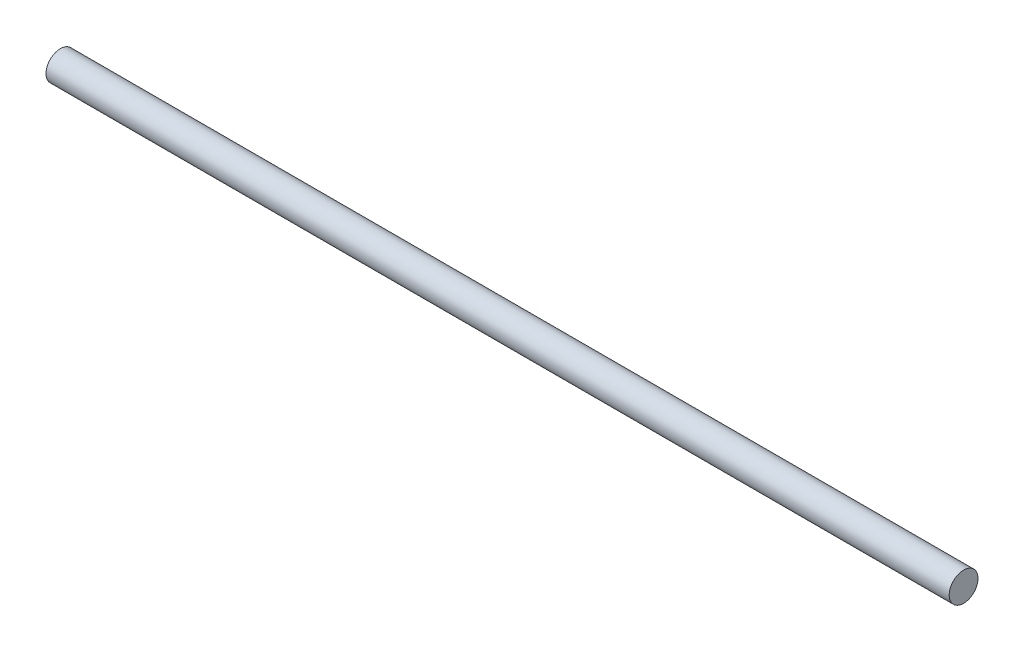
SolidWorks part; units mm, degrees
material "Aluminum Bronze"
ref_plane "Front Plane" through (0, 0, 0) normal (0, 0, 1) x (1, 0, 0)
ref_plane "Top Plane" through (0, 0, 0) normal (0, 1, 0) x (1, 0, 0)
ref_plane "Right Plane" through (0, 0, 0) normal (1, 0, 0) x (0, 0, -1)
sketch "Sketch1" plane through (0, 0, 0) normal (0, 1, 0) x (1, 0, 0)
  line L0 (0, 0) -> (407, 0)
  line L1 (0, 0) -> (0, 6.5)
  line L2 (0, 6.5) -> (407, 6.5)
  line L3 (407, 6.5) -> (407, 0)
  point P2 (0, 0)
  dimension "D1" = 407
  dimension "D2" = 6.5
revolve "Revolve1" add sketch "Sketch1" angle 360 about L0
